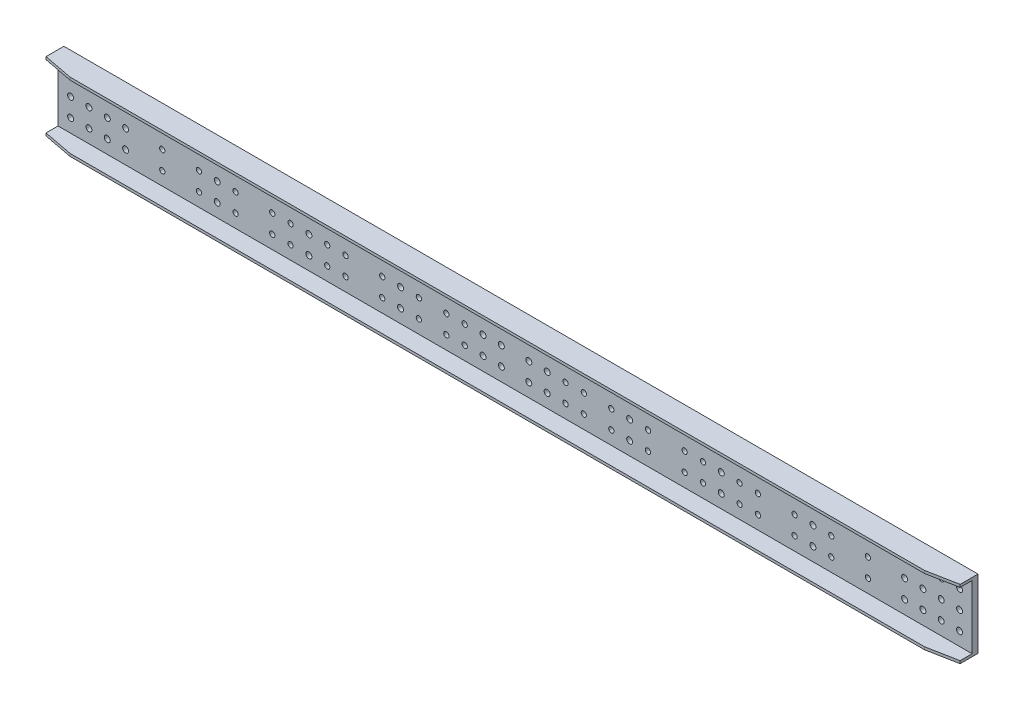
SolidWorks part; units mm, degrees
ref_plane "前视" through (0, 0, 0) normal (0, 0, 1) x (1, 0, 0)
ref_plane "上视" through (0, 0, 0) normal (0, 1, 0) x (1, 0, 0)
ref_plane "右视" through (0, 0, 0) normal (1, 0, 0) x (0, 0, -1)
sketch "草图1" plane through (0, 0, 0) normal (0, 0, 1) x (1, 0, 0)
  line L0 (0, 280.187) -> (0, -298.191) construction
  line L1 (-2057.2074, 0) -> (2116.7847, 0) construction
  line L2 (2116.7847, 80) -> (-2430.1435, 80) construction
  line L3 (-1995, 150) -> (1995, 150)
  line L5 (-1995, -150) -> (1995, -150)
  line L6 (1995, 150) -> (1995, -150)
  line L7 (-2430.1435, -80) -> (2116.7847, -80) construction
  line L8 (1940, 266.4652) -> (1940, -249.2739) construction
  line L9 (1860, -249.2739) -> (1860, 266.4652) construction
  line L10 (1060, 266.4652) -> (1060, -361.7988) construction
  line L11 (1780, 266.4652) -> (1780, -249.2739) construction
  line L12 (1780, -249.2739) -> (1700, -249.2739) construction
  line L13 (1700, -249.2739) -> (1700, 266.4652) construction
  line L14 (1540, 266.4652) -> (1540, -361.7988) construction
  line L15 (1380, 266.4652) -> (1380, -361.7988) construction
  line L16 (1220, -361.7988) -> (1220, 266.4652) construction
  line L17 (980, -361.7988) -> (980, 266.4652) construction
  line L18 (740, -361.7988) -> (740, 464.33) construction
  line L19 (820, 266.4652) -> (820, -361.7988) construction
  line L20 (580, -361.7988) -> (580, 266.4652) construction
  line L21 (420, -361.7988) -> (420, 266.4652) construction
  line L22 (300, -298.191) -> (300, 266.4652) construction
  line L23 (60, 280.187) -> (60, -298.191) construction
  line L24 (140, 280.187) -> (140, -298.191) construction
  line L25 (220, -298.191) -> (220, 280.187) construction
  line L26 (-1995, 150) -> (-1995, -150)
  circle A0 centre (1940, 80) radius 13
  circle A1 centre (1860, 80) radius 13
  circle A2 centre (1780, 80) radius 13
  circle A3 centre (1700, 80) radius 13
  circle A4 centre (1540, 80) radius 11.5
  circle A5 centre (1380, 80) radius 11.5
  circle A6 centre (1220, 80) radius 11.5
  circle A7 centre (1060, 80) radius 11.5
  circle A8 centre (980, 80) radius 11.5
  circle A9 centre (820, 80) radius 11.5
  circle A10 centre (740, 80) radius 11.5
  circle A11 centre (580, 80) radius 11.5
  circle A12 centre (980, 0) radius 11.5
  circle A13 centre (1060, 0) radius 11.5
  circle A14 centre (820, 0) radius 11.5
  circle A15 centre (740, 0) radius 11.5
  circle A16 centre (580, 0) radius 11.5
  circle A17 centre (1220, 0) radius 11.5
  circle A18 centre (1380, 0) radius 11.5
  circle A19 centre (1540, 0) radius 11.5
  circle A20 centre (1700, 0) radius 13
  circle A21 centre (1780, 0) radius 13
  circle A22 centre (1860, 0) radius 13
  circle A23 centre (1940, 0) radius 13
  circle A24 centre (420, 80) radius 11.5
  circle A25 centre (420, 0) radius 11.5
  circle A26 centre (300, 0) radius 11.5
  circle A27 centre (300, 80) radius 11.5
  circle A28 centre (220, 80) radius 11.5
  circle A29 centre (220, 0) radius 11.5
  circle A30 centre (140, 0) radius 13
  circle A31 centre (140, 80) radius 13
  circle A32 centre (60, 80) radius 13
  circle A33 centre (60, 0) radius 13
  circle A34 centre (1700, -80) radius 13
  circle A35 centre (1780, -80) radius 13
  circle A36 centre (1860, -80) radius 13
  circle A37 centre (1940, -80) radius 13
  circle A38 centre (580, -80) radius 11.5
  circle A39 centre (740, -80) radius 11.5
  circle A40 centre (820, -80) radius 11.5
  circle A41 centre (980, -80) radius 11.5
  circle A42 centre (1060, -80) radius 11.5
  circle A43 centre (1220, -80) radius 11.5
  circle A44 centre (1380, -80) radius 11.5
  circle A45 centre (1540, -80) radius 11.5
  circle A46 centre (220, -80) radius 11.5
  circle A47 centre (300, -80) radius 11.5
  circle A48 centre (420, -80) radius 11.5
  circle A49 centre (580, -80) radius 11.5
  circle A50 centre (60, -80) radius 13
  circle A51 centre (140, -80) radius 13
  circle A52 centre (-140, -80) radius 13
  circle A53 centre (-60, -80) radius 13
  circle A54 centre (-580, -80) radius 11.5
  circle A55 centre (-420, -80) radius 11.5
  circle A56 centre (-300, -80) radius 11.5
  circle A57 centre (-220, -80) radius 11.5
  circle A58 centre (-1540, -80) radius 11.5
  circle A59 centre (-1380, -80) radius 11.5
  circle A60 centre (-1220, -80) radius 11.5
  circle A61 centre (-1060, -80) radius 11.5
  circle A62 centre (-980, -80) radius 11.5
  circle A63 centre (-820, -80) radius 11.5
  circle A64 centre (-740, -80) radius 11.5
  circle A65 centre (-580, -80) radius 11.5
  circle A66 centre (-1940, -80) radius 13
  circle A67 centre (-1860, -80) radius 13
  circle A68 centre (-1780, -80) radius 13
  circle A69 centre (-1700, -80) radius 13
  circle A70 centre (-60, 0) radius 13
  circle A71 centre (-60, 80) radius 13
  circle A72 centre (-140, 80) radius 13
  circle A73 centre (-140, 0) radius 13
  circle A74 centre (-220, 0) radius 11.5
  circle A75 centre (-220, 80) radius 11.5
  circle A76 centre (-300, 80) radius 11.5
  circle A77 centre (-300, 0) radius 11.5
  circle A78 centre (-420, 0) radius 11.5
  circle A79 centre (-420, 80) radius 11.5
  circle A80 centre (-1940, 0) radius 13
  circle A81 centre (-1860, 0) radius 13
  circle A82 centre (-1780, 0) radius 13
  circle A83 centre (-1700, 0) radius 13
  circle A84 centre (-1540, 0) radius 11.5
  circle A85 centre (-1380, 0) radius 11.5
  circle A86 centre (-1220, 0) radius 11.5
  circle A87 centre (-580, 0) radius 11.5
  circle A88 centre (-740, 0) radius 11.5
  circle A89 centre (-820, 0) radius 11.5
  circle A90 centre (-1060, 0) radius 11.5
  circle A91 centre (-980, 0) radius 11.5
  circle A92 centre (-580, 80) radius 11.5
  circle A93 centre (-740, 80) radius 11.5
  circle A94 centre (-820, 80) radius 11.5
  circle A95 centre (-980, 80) radius 11.5
  circle A96 centre (-1060, 80) radius 11.5
  circle A97 centre (-1220, 80) radius 11.5
  circle A98 centre (-1380, 80) radius 11.5
  circle A99 centre (-1540, 80) radius 11.5
  circle A100 centre (-1700, 80) radius 13
  circle A101 centre (-1780, 80) radius 13
  circle A102 centre (-1860, 80) radius 13
  circle A103 centre (-1940, 80) radius 13
  dimension "D22" = 23
  dimension "D23" = 26
  dimension "D24" = 26
  dimension "D1" = 3990
  dimension "D2" = 300
  dimension "D3" = 70
  dimension "D4" = 80
  dimension "D5" = 55
  dimension "D6" = 80
  dimension "D7" = 80
  dimension "D8" = 80
  dimension "D9" = 455
  dimension "D10" = 160
  dimension "D11" = 160
  dimension "D12" = 160
  dimension "D13" = 80
  dimension "D14" = 160
  dimension "D15" = 80
  dimension "D16" = 160
  dimension "D17" = 160
  dimension "D18" = 120
  dimension "D19" = 60
  dimension "D20" = 80
  dimension "D21" = 80
extrude "基体-拉伸" add sketch "草图1" along normal blind 25.5
sketch "草图2" plane through (0, 0, 25.5) normal (0, 0, 1) x (1, 0, 0)
  line L0 (1995, -150) -> (1995, 150) construction
  line L1 (-1995, 150) -> (1995, 150)
  line L2 (-1995, 150) -> (-1995, 138.5)
  line L3 (-1995, 138.5) -> (1995, 138.5)
  line L4 (1995, 150) -> (1995, 138.5)
  line L5 (0, 0) -> (2507.3409, 0) construction
  line L6 (1995, -150) -> (1995, -138.5)
  line L7 (-1995, -138.5) -> (1995, -138.5)
  line L8 (-1995, -150) -> (-1995, -138.5)
  line L9 (-1995, -150) -> (1995, -150)
  dimension "D1" = 11.5
extrude "凸台-拉伸1" add sketch "草图2" along normal blind 77.5
sketch "草图3" plane through (0, 0, 0) normal (0, 0, -1) x (-1, 0, 0)
  line L0 (0, 0) -> (2381.8358, 0) construction
  line L1 (0, 348.8193) -> (0, -302.4645) construction
  line L2 (1300, 348.8193) -> (1300, -385.903) construction
  line L3 (1995, 150) -> (1995, -150) construction
  line L4 (900, 237.7997) -> (900, -385.903) construction
  line L5 (1265, 115) -> (1335, 115)
  line L6 (1265, 115) -> (1265, -115)
  line L7 (1265, -115) -> (1335, -115)
  line L8 (1335, 115) -> (1335, -115)
  line L9 (865, 115) -> (935, 115)
  line L10 (865, 115) -> (865, -115)
  line L11 (865, -115) -> (935, -115)
  line L12 (935, 115) -> (935, -115)
  line L13 (500, -385.903) -> (500, 237.7997) construction
  line L14 (-1265, 115) -> (-1335, 115)
  line L15 (535, -115) -> (465, -115)
  line L16 (535, -115) -> (535, 115)
  line L17 (535, 115) -> (465, 115)
  line L18 (465, -115) -> (465, 115)
  line L19 (-1335, 115) -> (-1335, -115)
  line L20 (-1265, 115) -> (-1265, -115)
  line L21 (-1265, -115) -> (-1335, -115)
  line L22 (-865, -115) -> (-935, -115)
  line L23 (-935, 115) -> (-935, -115)
  line L24 (-865, 115) -> (-935, 115)
  line L25 (-865, 115) -> (-865, -115)
  line L26 (-535, -115) -> (-535, 115)
  line L27 (-535, -115) -> (-465, -115)
  line L28 (-465, -115) -> (-465, 115)
  line L29 (-535, 115) -> (-465, 115)
  dimension "D1" = 695
  dimension "D2" = 70
  dimension "D3" = 230
  dimension "D4" = 400
  dimension "D5" = 70
  dimension "D6" = 230
  dimension "D7" = 400
  dimension "D8" = 70
  dimension "D9" = 230
extrude "凸台-拉伸2" add sketch "草图3" along normal blind 16
sketch "草图4" plane through (0, 0, 25.5) normal (0, 0, 1) x (1, 0, 0)
  line L0 (0, 0) -> (2249.2348, 0) construction
  line L1 (0, 0) -> (0, 1256.1111) construction
  line L2 (1300, 296.2067) -> (1300, -332.3633) construction
  line L3 (900, -332.3633) -> (900, 296.2067) construction
  line L4 (1995, -138.5) -> (1995, 138.5) construction
  line L5 (500, 260.05) -> (500, -332.3633) construction
  line L6 (1458.5104, 80) -> (376.6321, 80) construction
  circle A0 centre (1300, 80) radius 13
  circle A1 centre (900, 80) radius 13
  circle A2 centre (900, 0) radius 13
  circle A3 centre (1300, 0) radius 13
  circle A4 centre (900, -80) radius 13
  circle A5 centre (1300, -80) radius 13
  circle A6 centre (500, 80) radius 13
  circle A7 centre (500, 0) radius 13
  circle A8 centre (500, -80) radius 13
  circle A9 centre (-500, -80) radius 13
  circle A10 centre (-500, 0) radius 13
  circle A11 centre (-500, 80) radius 13
  circle A12 centre (-1300, -80) radius 13
  circle A13 centre (-900, -80) radius 13
  circle A14 centre (-1300, 0) radius 13
  circle A15 centre (-900, 0) radius 13
  circle A16 centre (-900, 80) radius 13
  circle A17 centre (-1300, 80) radius 13
  dimension "D5" = 26
  dimension "D1" = 695
  dimension "D2" = 400
  dimension "D3" = 400
  dimension "D4" = 80
extrude "切除-拉伸1" cut sketch "草图4" against normal through all
sketch "草图5" plane through (0, 150, 0) normal (0, 1, 0) x (-1, 0, 0)
  line L0 (-1995, 78) -> (-1995, 103)
  line L1 (-1995, 103) -> (-1995, 0) construction
  line L2 (-1995, 103) -> (-1865, 103)
  line L3 (-1995, 103) -> (1995, 103) construction
  line L4 (-1865, 103) -> (-1995, 78)
  line L5 (0, 174.8481) -> (0, -119.4889) construction
  line L6 (1865, 103) -> (1995, 78)
  line L7 (1995, 103) -> (1865, 103)
  line L8 (1995, 78) -> (1995, 103)
  dimension "D1" = 130
  dimension "D2" = 25
extrude "切除-拉伸2" cut sketch "草图5" against normal through all
